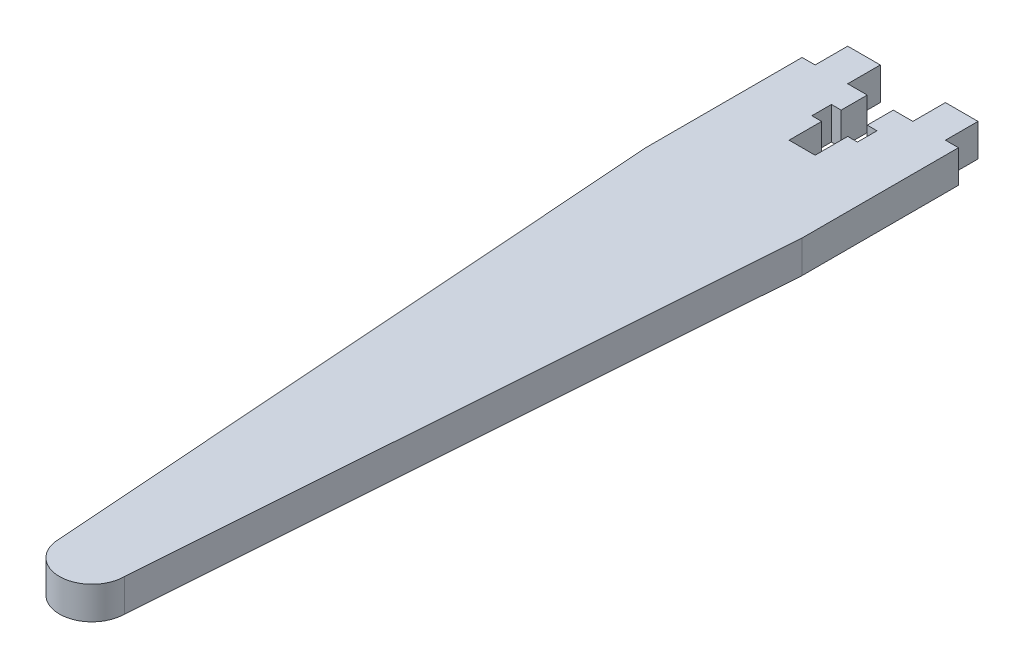
SolidWorks part; units mm, degrees
ref_plane "Front Plane" through (0, 0, 0) normal (0, 0, 1) x (1, 0, 0)
ref_plane "Top Plane" through (0, 0, 0) normal (0, 1, 0) x (1, 0, 0)
ref_plane "Right Plane" through (0, 0, 0) normal (1, 0, 0) x (0, 0, -1)
sketch "Sketch1" plane through (0, 0, 0) normal (0, 1, 0) x (1, 0, 0)
  line L0 (12, 24) -> (12, -102) construction
  line L2 (0, 0) -> (0, 24)
  line L3 (0, 24) -> (2, 24)
  line L4 (24, 0) -> (24, 24)
  line L5 (0, 0) -> (7, -97)
  line L6 (24, 0) -> (17, -97)
  line L7 (7, 29) -> (2, 29)
  line L9 (17, 24) -> (17, 29)
  line L10 (17, 29) -> (22, 29)
  line L11 (22, 24) -> (22, 29)
  line L12 (2, 24) -> (2, 29)
  line L14 (7, 24) -> (7, 29)
  line L15 (7, 24) -> (10, 24)
  line L16 (22, 24) -> (24, 24)
  line L17 (14, 17) -> (15.5, 17)
  line L18 (10, 12) -> (14, 12)
  line L19 (10, 12) -> (10, 17)
  line L21 (14, 12) -> (14, 17)
  line L22 (10, 12) -> (14, 24) construction
  line L23 (10, 24) -> (14, 12) construction
  line L24 (10, 20) -> (8.5, 20)
  line L26 (10, 17) -> (8.5, 17)
  line L27 (8.5, 20) -> (8.5, 17)
  line L28 (15.5, 20) -> (15.5, 17)
  line L29 (14, 20) -> (15.5, 20)
  line L31 (14, 24) -> (17, 24)
  line L32 (10, 20) -> (10, 24)
  line L33 (14, 20) -> (14, 24)
  arc A0 (7, -97) -> (17, -97) centre (12, -97) ccw
  point P20 (12, 18)
  dimension "D7" = 5
  dimension "D1" = 24
  dimension "D2" = 12
  dimension "D3" = 126
  dimension "D4" = 5
  dimension "D5" = 5
  dimension "D6" = 2
  dimension "D8" = 4
  dimension "D9" = 17
  dimension "D10" = 3
  dimension "D11" = 4
  dimension "D12" = 1.5
extrude "Boss-Extrude1" add sketch "Sketch1" along normal blind 5
